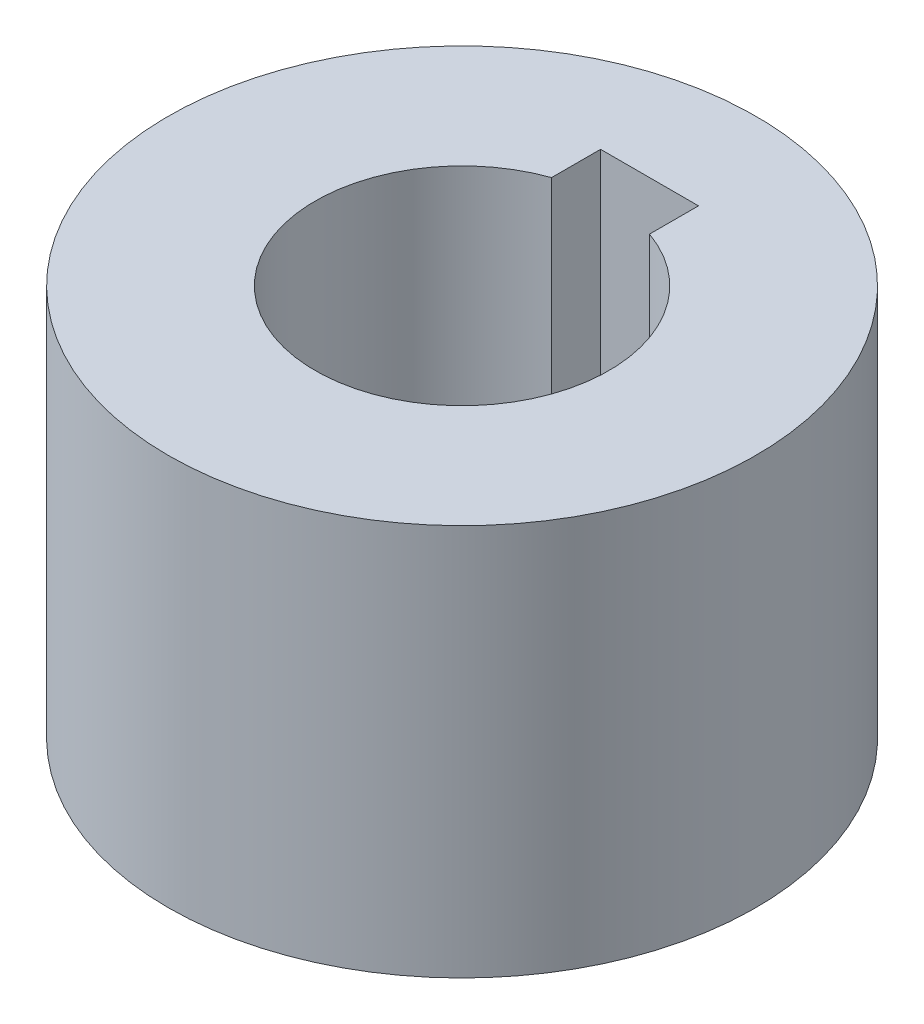
SolidWorks part; units mm, degrees
material "AISI 1045 Steel, cold drawn"
ref_plane "Frontal Plane" through (0, 0, 0) normal (0, 0, 1) x (1, 0, 0)
ref_plane "Horizontal Plane" through (0, 0, 0) normal (0, 1, 0) x (1, 0, 0)
ref_plane "Profile Plane" through (0, 0, 0) normal (1, 0, 0) x (0, 0, -1)
sketch "Sketch1" plane through (0, 0, 0) normal (0, 1, 0) x (1, 0, 0)
  line L0 (2.5, 7.0711) -> (2.5, 9.5711)
  line L1 (2.5, 9.5711) -> (-2.5, 9.5711)
  line L2 (-2.5, 9.5711) -> (-2.5, 7.0711)
  circle A1 centre (0, 0) radius 15
  arc A2 (-2.5, 7.0711) -> (2.5, 7.0711) centre (0, 0) ccw
  dimension "D1" = 30
  dimension "D2" = 2.5
  dimension "D3" = 7.5
  dimension "D4" = 5
extrude "Boss-Extrude1" add sketch "Sketch1" along normal blind 20
sketch "Sketch2" plane through (0, 20, 0) normal (0, 1, 0) x (1, 0, 0)
  line L0 (-2.5, 10) -> (2.5, 10)
  line L1 (2.5, 10) -> (2.5, 0)
  line L2 (2.5, 0) -> (-2.5, 0)
  line L3 (-2.5, 0) -> (-2.5, 10)
  point P2 (0, 0)
  dimension "D1" = 5
  dimension "D2" = 10
extrude "Cut-Extrude1" [suppressed] cut sketch "Sketch2" against normal blind 20
